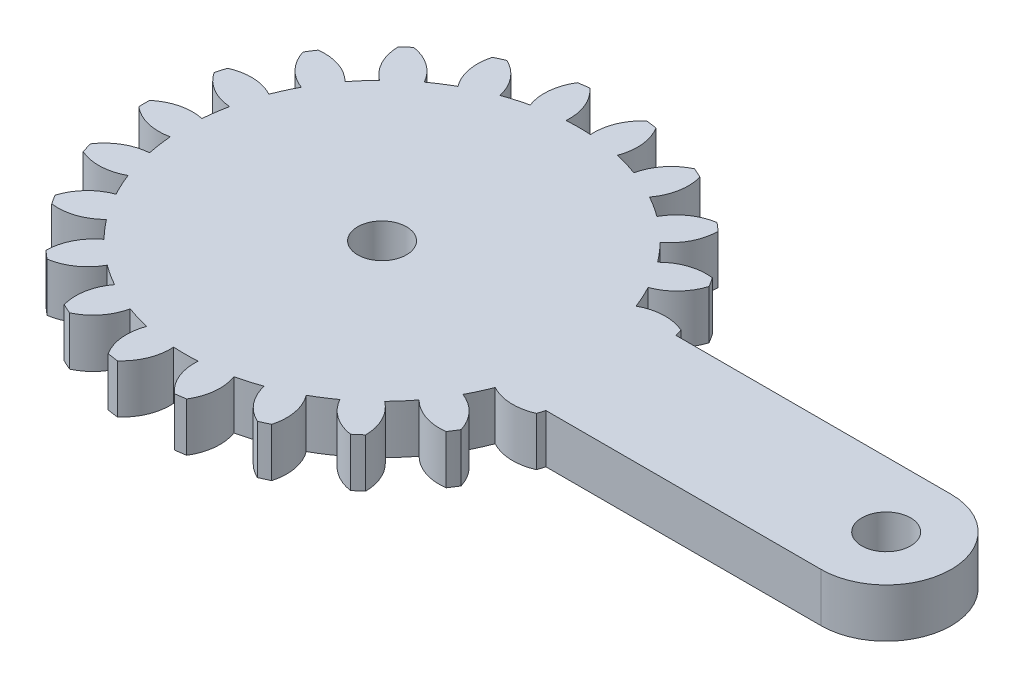
SolidWorks part; units mm, degrees
ref_plane "Ön Düzlem" through (0, 0, 0) normal (0, 0, 1) x (1, 0, 0)
ref_plane "Üst Düzlem" through (0, 0, 0) normal (0, 1, 0) x (1, 0, 0)
ref_plane "Sağ Düzlem" through (0, 0, 0) normal (1, 0, 0) x (0, 0, -1)
sketch "Çizim2" plane through (0, 0, 0) normal (0, 1, 0) x (1, 0, 0)
  circle A0 centre (0, 0) radius 1.5
  circle A1 centre (0, 0) radius 14.63
  dimension "D1" = 3
  dimension "D2" = 29.26
extrude "Yükseklik-Ekstrüzyon1" add sketch "Çizim2" along normal blind 3
sketch "Çizim3" plane through (0, 3, 0) normal (0, 1, 0) x (1, 0, 0)
  line L0 (0, 12.09) -> (0, 18.0204) construction
  arc A0 (0.75, 12.0667) -> (-0.75, 12.0667) centre (0, 0) ccw
  arc A1 (-1.75, 14.525) -> (-0.75, 12.0667) centre (-3.7423, 12.282) cw
  circle A2 centre (0, 0) radius 14.63 construction
  arc A3 (1.75, 14.525) -> (0.75, 12.0667) centre (3.7423, 12.282) ccw
  arc A4 (1.75, 14.525) -> (-1.75, 14.525) centre (0, 0) ccw
  dimension "D2" = 3
  dimension "D3" = 1.5
  dimension "D4" = 3.5
extrude "Kes-Ekstrüzyon1" cut sketch "Çizim3" against normal blind 3
pattern_circular "Dairesel Kaplama1" count 22 over 360 about axis through (0, 0, 0) along (0, 1, 0) of "Kes-Ekstrüzyon1"
sketch "Çizim4" plane through (0, 3, 0) normal (0, 1, 0) x (1, 0, 0)
  line L0 (0, 0) -> (4.5547, 0) construction
  line L1 (31, 4) -> (4.5547, 4)
  line L2 (4.5547, 4) -> (4.5547, -4)
  line L3 (4.5547, -4) -> (31, -4)
  line L4 (27, 0) -> (31, 0) construction
  circle A0 centre (31, 0) radius 1.5
  arc A1 (31, -4) -> (31, 4) centre (31, 0) ccw
  dimension "D1" = 3
  dimension "D2" = 8
  dimension "D3" = 31
extrude "Yükseklik-Ekstrüzyon2" add sketch "Çizim4" against normal blind 3
